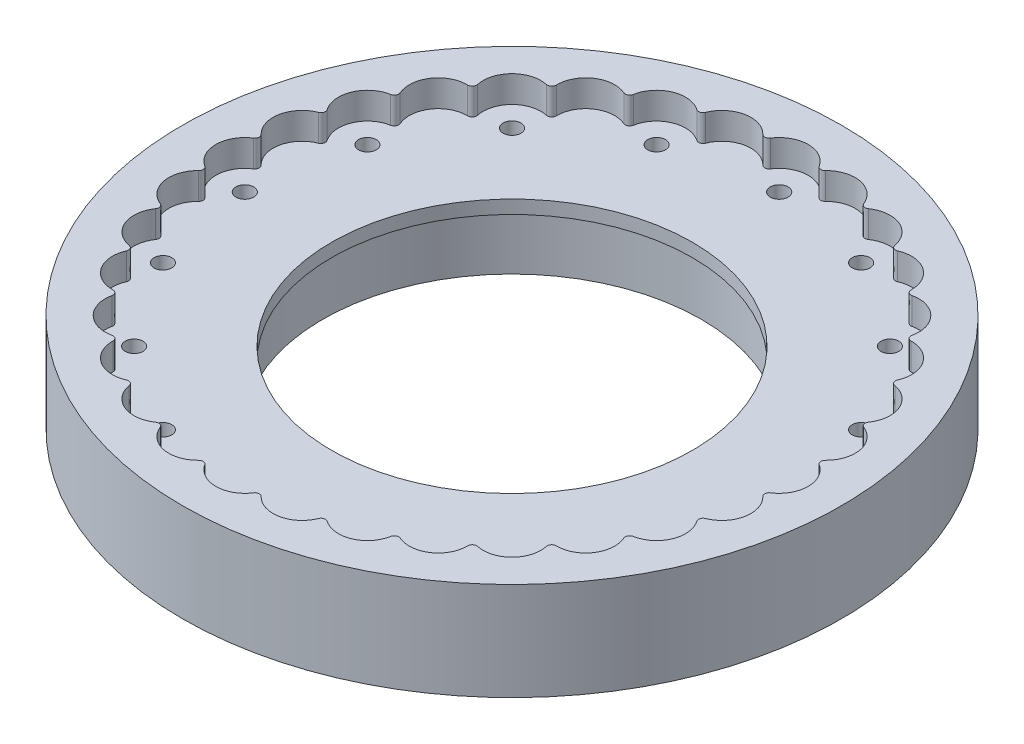
SolidWorks part; units mm, degrees
material "尼龙 101"
ref_plane "前视基准面" through (0, 0, 0) normal (0, 0, 1) x (1, 0, 0)
ref_plane "上视基准面" through (0, 0, 0) normal (0, 1, 0) x (1, 0, 0)
ref_plane "右视基准面" through (0, 0, 0) normal (1, 0, 0) x (0, 0, -1)
sketch "草图1" plane through (0, 0, 0) normal (0, 1, 0) x (1, 0, 0)
  line L0 (-3, 0) -> (-61.8471, 11.7054) construction
  line L1 (-63, 0) -> (-3, 0) construction
  line L2 (-3, 0) -> (-62.7111, 5.881) construction
  line L3 (-61.8471, 11.7054) -> (-80.5752, 15.4307) construction
  line L4 (-63, 0) -> (-84.6703, 0) construction
  arc A23 (51.1029, 1.1255) -> (51, 0) centre (57.2058, 0) ccw construction
  circle A26 centre (-45.4264, 42.4264) radius 6.5 construction
  circle A27 centre (-25.961, 55.4328) radius 6.5 construction
  circle A28 centre (-3, 60) radius 6.5 construction
  circle A29 centre (19.961, 55.4328) radius 6.5 construction
  circle A30 centre (39.4264, 42.4264) radius 6.5 construction
  circle A31 centre (52.4328, 22.961) radius 6.5 construction
  circle A32 centre (57, 0) radius 6.5 construction
  circle A33 centre (52.4328, -22.961) radius 6.5 construction
  circle A34 centre (39.4264, -42.4264) radius 6.5 construction
  circle A35 centre (19.961, -55.4328) radius 6.5 construction
  circle A36 centre (-3, -60) radius 6.5 construction
  circle A37 centre (-25.961, -55.4328) radius 6.5 construction
  circle A38 centre (-45.4264, -42.4264) radius 6.5 construction
  circle A39 centre (-58.4328, -22.961) radius 6.5 construction
  circle A40 centre (-3, 0) radius 74
  circle A42 centre (-3, 0) radius 60 construction
  arc A46 (-68.2222, 12.9735) -> (-65.1785, 6.1241) centre (-61.8471, 11.7054) ccw
  arc A48 (-69.5, 0) -> (-65.1785, 6.1241) centre (-63, 0) cw
  arc A49 (-68.2222, 12.9735) -> (-62.789, 18.1368) centre (-61.8471, 11.7054) cw
  arc A50 (-64.438, 25.4484) -> (-62.789, 18.1368) centre (-58.4328, 22.961) ccw
  arc A51 (-64.438, 25.4484) -> (-58.1019, 29.4526) centre (-58.4328, 22.961) cw
  arc A52 (-58.2927, 36.9454) -> (-58.1019, 29.4526) centre (-52.8882, 33.3342) ccw
  arc A53 (-58.2927, 36.9454) -> (-51.2972, 39.6365) centre (-52.8882, 33.3342) cw
  arc A54 (-50.0226, 47.0226) -> (-51.2972, 39.6365) centre (-45.4264, 42.4264) ccw
  arc A55 (-50.0226, 47.0226) -> (-42.6365, 48.2972) centre (-45.4264, 42.4264) cw
  arc A56 (-39.9454, 55.2927) -> (-42.6365, 48.2972) centre (-36.3342, 49.8882) ccw
  arc A57 (-39.9454, 55.2927) -> (-32.4526, 55.1019) centre (-36.3342, 49.8882) cw
  arc A58 (-28.4484, 61.438) -> (-32.4526, 55.1019) centre (-25.961, 55.4328) ccw
  arc A59 (-28.4484, 61.438) -> (-21.1368, 59.789) centre (-25.961, 55.4328) cw
  arc A60 (-15.9735, 65.2222) -> (-21.1368, 59.789) centre (-14.7054, 58.8471) ccw
  arc A61 (-15.9735, 65.2222) -> (-9.1241, 62.1785) centre (-14.7054, 58.8471) cw
  arc A62 (-3, 66.5) -> (-9.1241, 62.1785) centre (-3, 60) ccw
  arc A63 (-3, 66.5) -> (3.1241, 62.1785) centre (-3, 60) cw
  arc A64 (9.9735, 65.2222) -> (3.1241, 62.1785) centre (8.7054, 58.8471) ccw
  arc A65 (9.9735, 65.2222) -> (15.1368, 59.789) centre (8.7054, 58.8471) cw
  arc A66 (22.4484, 61.438) -> (15.1368, 59.789) centre (19.961, 55.4328) ccw
  arc A67 (22.4484, 61.438) -> (26.4526, 55.1019) centre (19.961, 55.4328) cw
  arc A68 (33.9454, 55.2927) -> (26.4526, 55.1019) centre (30.3342, 49.8882) ccw
  arc A69 (33.9454, 55.2927) -> (36.6365, 48.2972) centre (30.3342, 49.8882) cw
  arc A70 (44.0226, 47.0226) -> (36.6365, 48.2972) centre (39.4264, 42.4264) ccw
  arc A71 (44.0226, 47.0226) -> (45.2972, 39.6365) centre (39.4264, 42.4264) cw
  arc A72 (52.2927, 36.9454) -> (45.2972, 39.6365) centre (46.8882, 33.3342) ccw
  arc A73 (52.2927, 36.9454) -> (52.1019, 29.4526) centre (46.8882, 33.3342) cw
  arc A74 (58.438, 25.4484) -> (52.1019, 29.4526) centre (52.4328, 22.961) ccw
  arc A75 (58.438, 25.4484) -> (56.789, 18.1368) centre (52.4328, 22.961) cw
  arc A76 (62.2222, 12.9735) -> (56.789, 18.1368) centre (55.8471, 11.7054) ccw
  arc A77 (62.2222, 12.9735) -> (59.1785, 6.1241) centre (55.8471, 11.7054) cw
  arc A78 (63.5, 0) -> (59.1785, 6.1241) centre (57, 0) ccw
  arc A79 (63.5, 0) -> (59.1785, -6.1241) centre (57, 0) cw
  arc A80 (62.2222, -12.9735) -> (59.1785, -6.1241) centre (55.8471, -11.7054) ccw
  arc A81 (62.2222, -12.9735) -> (56.789, -18.1368) centre (55.8471, -11.7054) cw
  arc A82 (58.438, -25.4484) -> (56.789, -18.1368) centre (52.4328, -22.961) ccw
  arc A83 (58.438, -25.4484) -> (52.1019, -29.4526) centre (52.4328, -22.961) cw
  arc A84 (52.2927, -36.9454) -> (52.1019, -29.4526) centre (46.8882, -33.3342) ccw
  arc A85 (52.2927, -36.9454) -> (45.2972, -39.6365) centre (46.8882, -33.3342) cw
  arc A86 (44.0226, -47.0226) -> (45.2972, -39.6365) centre (39.4264, -42.4264) ccw
  arc A87 (44.0226, -47.0226) -> (36.6365, -48.2972) centre (39.4264, -42.4264) cw
  arc A88 (33.9454, -55.2927) -> (36.6365, -48.2972) centre (30.3342, -49.8882) ccw
  arc A89 (33.9454, -55.2927) -> (26.4526, -55.1019) centre (30.3342, -49.8882) cw
  arc A90 (22.4484, -61.438) -> (26.4526, -55.1019) centre (19.961, -55.4328) ccw
  arc A91 (22.4484, -61.438) -> (15.1368, -59.789) centre (19.961, -55.4328) cw
  arc A92 (9.9735, -65.2222) -> (15.1368, -59.789) centre (8.7054, -58.8471) ccw
  arc A93 (9.9735, -65.2222) -> (3.1241, -62.1785) centre (8.7054, -58.8471) cw
  arc A94 (-3, -66.5) -> (3.1241, -62.1785) centre (-3, -60) ccw
  arc A95 (-3, -66.5) -> (-9.1241, -62.1785) centre (-3, -60) cw
  arc A96 (-15.9735, -65.2222) -> (-9.1241, -62.1785) centre (-14.7054, -58.8471) ccw
  arc A97 (-15.9735, -65.2222) -> (-21.1368, -59.789) centre (-14.7054, -58.8471) cw
  arc A98 (-28.4484, -61.438) -> (-21.1368, -59.789) centre (-25.961, -55.4328) ccw
  arc A99 (-28.4484, -61.438) -> (-32.4526, -55.1019) centre (-25.961, -55.4328) cw
  arc A100 (-39.9454, -55.2927) -> (-32.4526, -55.1019) centre (-36.3342, -49.8882) ccw
  arc A101 (-39.9454, -55.2927) -> (-42.6365, -48.2972) centre (-36.3342, -49.8882) cw
  arc A102 (-50.0226, -47.0226) -> (-42.6365, -48.2972) centre (-45.4264, -42.4264) ccw
  arc A103 (-50.0226, -47.0226) -> (-51.2972, -39.6365) centre (-45.4264, -42.4264) cw
  arc A104 (-58.2927, -36.9454) -> (-51.2972, -39.6365) centre (-52.8882, -33.3342) ccw
  arc A105 (-58.2927, -36.9454) -> (-58.1019, -29.4526) centre (-52.8882, -33.3342) cw
  arc A106 (-64.438, -25.4484) -> (-58.1019, -29.4526) centre (-58.4328, -22.961) ccw
  arc A107 (-64.438, -25.4484) -> (-62.789, -18.1368) centre (-58.4328, -22.961) cw
  arc A108 (-68.2222, -12.9735) -> (-62.789, -18.1368) centre (-61.8471, -11.7054) ccw
  arc A109 (-68.2222, -12.9735) -> (-65.1785, -6.1241) centre (-61.8471, -11.7054) cw
  arc A110 (-69.5, 0) -> (-65.1785, -6.1241) centre (-63, 0) ccw
  spline S0 degree 4 poles (46.5379, 25.7372) (46.4141, 25.4265) (46.2214, 24.8455) (46.0453, 23.97) (46.0305, 22.7997) (46.2124, 21.7023) (46.5944, 20.6304) (47.1781, 19.6256) (47.8576, 18.8426) (48.5552, 18.26) (49.1821, 17.8581) (49.7006, 17.5881) (50.2292, 17.3676) (50.7615, 17.19) (51.2467, 17.0604) (51.6756, 16.9442) (52.1157, 16.7843) (52.5471, 16.5748) (53.011, 16.2813) (53.5578, 15.8417) (54.0998, 15.2905) (54.8463, 14.3188) (55.4686, 13.069) (55.8643, 11.6469) (55.963, 10.2274) (55.8937, 9.2229) (55.7314, 8.3871) (55.5299, 7.7199) (55.2718, 7.103) (54.9628, 6.5421) (54.6, 6.0376) (54.1839, 5.6019) (53.729, 5.2398) (53.2959, 4.8829) (52.8541, 4.4702) (52.42, 3.9903) (52.024, 3.4526) (51.6787, 2.8581) (51.4223, 2.2845) (51.2601, 1.8044) (51.1585, 1.4093) (51.0974, 1.1068) (51.0631, 0.8925) (51.0397, 0.7088) (51.0244, 0.5571) (51.0146, 0.4347) (51.0053, 0.2754) (51, 0.0893) (50.9991, -0.0325) (51.0033, -0.2118) (51.0104, -0.3723) (51.0237, -0.5582) (51.0467, -0.7767) (51.0935, -1.1015) (51.1814, -1.5223) (51.3208, -2.0042) (51.5289, -2.5363) (51.7967, -3.0719) (52.1288, -3.6024) (52.5013, -4.0845) (52.9041, -4.5182) (53.3092, -4.8924) (53.702, -5.2183) (54.1137, -5.5446) (54.4991, -5.9242) (54.8403, -6.3624) (55.1378, -6.8475) (55.4263, -7.4461) (55.6786, -8.1632) (55.8744, -9.0445) (55.9607, -10.0854) (55.902, -11.1727) (55.6837, -12.2843) (55.3275, -13.3134) (54.856, -14.2458) (54.3439, -14.9904) (53.8416, -15.5634) (53.3534, -16.0123) (52.9029, -16.3539) (52.4611, -16.6202) (52.0385, -16.8165) (51.6463, -16.9514) (51.2956, -17.047) (50.9168, -17.149) (50.5132, -17.271) (50.0892, -17.4238) (49.6494, -17.6158) (49.0833, -17.9121) (48.4035, -18.3646) (47.6718, -19.0234) (46.9704, -19.9376) (46.436, -20.9941) (46.1117, -22.1269) (46.0124, -23.2422) (46.1036, -24.2957) (46.3078, -25.1327) (46.5435, -25.7773) (46.7581, -26.2481) (46.914, -26.5603) (47.0718, -26.8714) (47.2362, -27.2113) (47.3981, -27.6474) (47.5243, -28.1866) (47.5924, -28.7663) (47.6026, -29.4384) (47.5301, -30.1963) (47.3381, -31.083) (46.9787, -32.0726) (46.3109, -33.3348) (45.4042, -34.4509) (44.347, -35.3429) (43.2664, -35.9432) (42.5437, -36.236) (41.8612, -36.4237) (41.3142, -36.5096) (40.8308, -36.531) (40.3614, -36.5031) (39.9223, -36.4373) (39.429, -36.3568) (38.8747, -36.2998) (38.3065, -36.2819) (37.7271, -36.3124) (36.99, -36.4173) (36.0942, -36.6625) (35.1251, -37.109) (34.1566, -37.8104) (33.3468, -38.6733) (32.7332, -39.6305) (32.365, -40.5265) (32.1683, -41.3066) (32.0778, -41.929) (32.0418, -42.3994) (32.0358, -42.8432) (32.0497, -43.2589) (32.0714, -43.6463) (32.0826, -44.0066) (32.0632, -44.417) (31.9953, -44.8732) (31.8342, -45.5014) (31.5334, -46.239) (31.0863, -47.0125) (30.2784, -48.0426) (29.2767, -48.9308) (28.0765, -49.659) (26.7888, -50.1357) (25.7857, -50.3555) (24.9142, -50.4297) (24.1917, -50.4106) (23.5355, -50.3216) (22.9511, -50.1778) (22.4651, -49.9941) (22.0782, -49.7927) (21.7795, -49.6071) (21.5546, -49.4615) (21.2725, -49.2809) (20.928, -49.0738) (20.5013, -48.8474) (19.9846, -48.6223) (19.434, -48.4365) (18.8519, -48.2978) (18.1069, -48.1932) (17.1874, -48.1824) (16.1397, -48.343) (15.0305, -48.7429) (14.036, -49.3297) (13.2407, -50.0153) (12.6167, -50.7563) (12.1857, -51.4457) (11.8991, -52.0281) (11.6878, -52.5417) (11.526, -52.9744) (11.3359, -53.4202) (11.0812, -53.8588) (10.7673, -54.2823) (10.3968, -54.6857) (9.919, -55.118) (9.3192, -55.5548) (8.5533, -55.9873) (7.6098, -56.3665) (6.5728, -56.6314) (5.4562, -56.7578) (4.3706, -56.7287) (3.3372, -56.5582) (2.4735, -56.2932) (1.7785, -55.9874) (1.2003, -55.6539) (0.7315, -55.3183) (0.3297, -54.9579) (-0.0031, -54.5808) (-0.2691, -54.1986) (-0.4996, -53.8375) (-0.799, -53.3974) (-1.189, -52.8945) (-1.7518, -52.3018) (-2.5487, -51.6731) (-3.5127, -51.1471) (-4.6341, -50.7864) (-5.8197, -50.642) (-6.9885, -50.7226) (-8.0385, -50.9971) (-8.9494, -51.4066) (-9.6407, -51.8441) (-10.1588, -52.2535) (-10.5841, -52.6447) (-10.8891, -52.9527) (-11.1549, -53.2129) (-11.4512, -53.4676) (-11.7835, -53.7079) (-12.2085, -53.9529) (-12.7305, -54.1823) (-13.3637, -54.3899) (-14.1104, -54.5474) (-15.0125, -54.6285) (-16.0592, -54.5811) (-17.1309, -54.3847) (-18.204, -54.0281) (-19.1516, -53.5586) (-19.9687, -53.0108) (-20.7121, -52.3651) (-21.2707, -51.7315) (-21.7011, -51.088) (-21.9912, -50.4891) (-22.155, -50.0306) (-22.2585, -49.5926) (-22.3227, -49.1847) (-22.3899, -48.7713) (-22.4739, -48.3546) (-22.6085, -47.8313) (-22.8424, -47.1546) (-23.2318, -46.3575) (-23.8544, -45.4791) (-24.6871, -44.6677) (-25.6692, -44.0188) (-26.6389, -43.6178) (-27.5154, -43.4106) (-28.2524, -43.3323) (-28.8472, -43.3254) (-29.4322, -43.3725) (-30.003, -43.4693) (-30.5614, -43.6126) (-31.0373, -43.7728) (-31.4387, -43.9271) (-31.8427, -44.0792) (-32.2579, -44.2061) (-32.7611, -44.2963) (-33.347, -44.3297) (-34.0225, -44.2957) (-34.7782, -44.1696) (-35.6535, -43.9116) (-36.6179, -43.4757) (-37.7704, -42.7458) (-38.7933, -41.7926) (-39.611, -40.6949) (-40.1395, -39.6116) (-40.3976, -38.8546) (-40.5426, -38.2008) (-40.6112, -37.6643) (-40.6244, -37.1634) (-40.5888, -36.7038) (-40.513, -36.2896) (-40.4169, -35.9209) (-40.2866, -35.4356) (-40.1742, -34.9317) (-40.0977, -34.4072) (-40.055, -33.7098) (-40.0823, -32.9434) (-40.242, -32.0266) (-40.6161, -30.9905) (-41.1976, -29.9862) (-41.9718, -29.089) (-42.813, -28.4312) (-43.6374, -27.9836) (-44.3396, -27.7115) (-44.9036, -27.5499) (-45.4676, -27.4392) (-46.0267, -27.3726) (-46.531, -27.3441) (-46.9786, -27.3217) (-47.4491, -27.2608) (-47.924, -27.1472) (-48.4491, -26.9557) (-49.0877, -26.6351) (-49.7446, -26.2008) (-50.6925, -25.3887) (-51.5674, -24.2757) (-52.2468, -22.9494) (-52.6787, -21.3876) (-52.7938, -20.2381) (-52.7415, -19.2513) (-52.5869, -18.4477) (-52.4194, -17.8829) (-52.2031, -17.3696) (-51.9445, -16.9122) (-51.6489, -16.5156) (-51.3534, -16.1582) (-51.0001, -15.7004) (-50.6155, -15.1236) (-50.215, -14.3486) (-49.8747, -13.3327) (-49.7104, -12.2175) (-49.7626, -11.0381) (-50.0365, -9.8863) (-50.5035, -8.838) (-51.1016, -7.968) (-51.767, -7.2731) (-52.3746, -6.7892) (-52.8873, -6.4554) (-53.352, -6.1961) (-53.7558, -5.9914) (-54.1811, -5.7701) (-54.6019, -5.4873) (-55.0061, -5.1386) (-55.388, -4.7281) (-55.8029, -4.184) (-56.2163, -3.4883) (-56.5934, -2.616) (-56.8794, -1.5636) (-57.0192, -0.4644) (-57.0056, 0.6609) (-56.8431, 1.7289) (-56.5512, 2.7215) (-56.1864, 3.5378) (-55.8005, 4.1844) (-55.4038, 4.7095) (-55.0213, 5.1241) (-54.6067, 5.4849) (-54.1623, 5.7832) (-53.6999, 6.019) (-53.2522, 6.2482) (-52.7801, 6.5213) (-52.2943, 6.8511) (-51.7159, 7.3247) (-51.0958, 7.9792) (-50.5093, 8.8286) (-50.0309, 9.8972) (-49.7598, 11.0441) (-49.7119, 12.2402) (-49.8762, 13.3181) (-50.1782, 14.2422) (-50.5297, 14.9617) (-50.8583, 15.4946) (-51.1503, 15.8971) (-51.3791, 16.1864) (-51.6107, 16.4733) (-51.8529, 16.7821) (-52.1097, 17.1857) (-52.3487, 17.6957) (-52.5356, 18.2511) (-52.6793, 18.8847) (-52.763, 19.5933) (-52.7701, 20.454) (-52.6495, 21.4551) (-52.3771, 22.4981) (-51.9324, 23.5552) (-51.3729, 24.4924) (-50.7281, 25.3031) (-49.9819, 26.0211) (-49.2536, 26.5457) (-48.5459, 26.9194) (-47.9336, 27.1417) (-47.4843, 27.2532) (-47.0763, 27.3113) (-46.7156, 27.3356) (-46.3267, 27.3549) (-45.9101, 27.3865) (-45.4675, 27.4417) (-45.0015, 27.5305) (-44.3901, 27.6912) (-43.6335, 27.9763) (-42.7808, 28.447) (-41.8967, 29.1702) (-41.1366, 30.0712) (-40.5592, 31.0993) (-40.2209, 32.1183) (-40.0728, 33.0677) (-40.0563, 33.8576) (-40.1067, 34.4963) (-40.2075, 35.0962) (-40.3418, 35.6563) (-40.4802, 36.1417) (-40.5678, 36.5674) (-40.6138, 37.0012) (-40.6228, 37.442) (-40.5823, 37.957) (-40.4594, 38.6248) (-40.2357, 39.3609) (-39.8665, 40.1996) (-39.3093, 41.105) (-38.5945, 41.9688) (-37.7193, 42.7584) (-36.7891, 43.3798) (-35.8364, 43.84) (-34.9691, 44.1216) (-34.2184, 44.27) (-33.545, 44.3264) (-32.9584, 44.3148) (-32.4068, 44.2406) (-31.8988, 44.1039) (-31.436, 43.9247) (-30.9987, 43.7594) (-30.449, 43.5789) (-29.7785, 43.4164) (-28.9191, 43.3079) (-27.8569, 43.3383) (-26.757, 43.5667) (-25.6692, 44.0207) (-24.684, 44.6726) (-23.8603, 45.4711) (-23.2924, 46.269) (-22.9216, 46.9921) (-22.6921, 47.5848) (-22.5511, 48.0407) (-22.4467, 48.4768) (-22.3698, 48.8893) (-22.3091, 49.2753) (-22.2491, 49.6326) (-22.1523, 50.0344) (-21.9978, 50.4724) (-21.7764, 50.9361) (-21.482, 51.4161) (-21.0854, 51.9441) (-20.5679, 52.4988) (-19.8818, 53.0808) (-19.0059, 53.6423) (-18.0145, 54.1038) (-16.9178, 54.4377) (-15.8549, 54.6016) (-14.8516, 54.6199) (-13.9999, 54.5266) (-13.3064, 54.3732) (-12.6928, 54.1684) (-12.1604, 53.929) (-11.6778, 53.643) (-11.3015, 53.3503) (-11.0187, 53.0802) (-10.7585, 52.8208) (-10.4964, 52.563) (-10.1304, 52.2302) (-9.6404, 51.8467) (-8.9692, 51.4191) (-8.0913, 51.0165) (-7.0449, 50.7309) (-5.8547, 50.64) (-4.6842, 50.7757) (-3.5637, 51.1281) (-2.6486, 51.6152) (-1.9245, 52.1589) (-1.3864, 52.6821) (-1.0025, 53.1293) (-0.6771, 53.5709) (-0.3982, 53.9941) (-0.1162, 54.4338) (0.2241, 54.8506) (0.6253, 55.2305) (1.0772, 55.5722) (1.6416, 55.9168) (2.3267, 56.2378) (3.1797, 56.5198) (4.2016, 56.7104) (5.2866, 56.7631) (6.4144, 56.66) (7.4766, 56.4105) (8.4562, 56.0346) (9.2521, 55.5984) (9.8752, 55.154) (10.3724, 54.7109) (10.7582, 54.2944) (11.0488, 53.9039) (11.2569, 53.556) (11.4258, 53.2121) (11.5625, 52.8773) (11.7103, 52.4828) (11.9209, 51.9813) (12.1928, 51.4389) (12.5985, 50.7878) (13.1988, 50.0572) (13.9876, 49.3606) (14.9807, 48.7666) (16.0976, 48.3562) (17.2682, 48.1654) (18.3284, 48.1967) (19.244, 48.3746) (19.9605, 48.6113) (20.5094, 48.8503) (21.0146, 49.1208) (21.4217, 49.3736) (21.7644, 49.5994) (22.061, 49.7799) (22.3115, 49.9131) (22.6419, 50.061) (23.0591, 50.2055) (23.561, 50.3258) (24.2389, 50.4157) (25.0178, 50.4296) (25.9392, 50.3338) (26.9809, 50.0765) (28.32, 49.538) (29.5308, 48.7459) (30.5312, 47.7796) (31.2405, 46.7598) (31.6056, 46.0664) (31.8606, 45.4025) (31.9997, 44.8638) (32.0673, 44.3826) (32.0836, 43.9106) (32.0614, 43.4651) (32.0348, 42.9634) (32.0393, 42.4031) (32.0856, 41.8333) (32.182, 41.2578) (32.3713, 40.5332) (32.7195, 39.6672) (33.2739, 38.7585) (34.0745, 37.8856) (35.0067, 37.1899) (35.9971, 36.6968) (36.8947, 36.432) (37.6572, 36.3175) (38.3592, 36.2814) (38.8924, 36.299) (39.4083, 36.3557) (39.9069, 36.4338) (40.2839, 36.4925) (40.7045, 36.5289) (41.1671, 36.5204) (41.6662, 36.4586) (42.1957, 36.337) (42.8347, 36.1271) (43.5651, 35.7931) (44.3633, 35.2983) (45.188, 34.6103) (46.1279, 33.5815) (46.8494, 32.4192) (47.337, 31.1804) (47.5589, 30.0001) (47.6088, 29.2392) (47.5762, 28.5668) (47.4863, 27.9897) (47.349, 27.4996) (47.1843, 27.0997) (46.9931, 26.7142) (46.7974, 26.333) (46.5867, 25.8792) (46.3831, 25.3424) (46.2237, 24.7888) (46.1116, 24.2161) (46.0512, 23.6278) (46.0449, 22.8915) (46.1493, 22.0014) (46.4363, 20.9879) (46.9745, 19.9251) (47.7041, 18.9865) (48.4998, 18.2848) (49.285, 17.7868) (49.9686, 17.4674) (50.5132, 17.2692) (51.0085, 17.1221) (51.4478, 17.0085) (51.912, 16.8692) (52.3842, 16.6623) (52.8554, 16.3864) (53.3182, 16.0422) (53.7955, 15.609) (54.2709, 15.0778) (54.7703, 14.3808) (55.2461, 13.4987) (55.6279, 12.4872) (55.8786, 11.3552) (55.9619, 10.2497) (55.8955, 9.1942) (55.7154, 8.2993) (55.4758, 7.57) (55.1961, 6.9567) (54.9032, 6.4546) (54.5797, 6.0202) (54.2341, 5.6566) (53.8813, 5.3592) (53.5523, 5.0956) (53.2287, 4.8192) (52.9161, 4.5249) (52.5434, 4.1311) (52.1808, 3.6766) (51.8445, 3.1605) (51.579, 2.6398) (51.4091, 2.232) (51.2991, 1.9115) (51.2333, 1.6918) (51.1844, 1.5058) (51.1465, 1.3427) (51.1136, 1.185) (51.0924, 1.0702) (51.0671, 0.9132) (51.0452, 0.7545) (51.0245, 0.5678) (51.0076, 0.3469) (50.9975, 0.0834) (51.0008, -0.2155) (51.0227, -0.5894) (51.078, -1.035) (51.1839, -1.5486) (51.4036, -2.2603) (51.7236, -2.9659) (52.1483, -3.6478) (52.6384, -4.2427) (53.0557, -4.6645) (53.4116, -4.9778) (53.6865, -5.203) (53.9622, -5.4272) (54.1981, -5.6295) (54.4282, -5.8597) (54.6955, -6.1751) (54.9531, -6.5374) (55.213, -6.9884) (55.4926, -7.613) (55.7287, -8.3512) (55.9038, -9.2579) (55.962, -10.3279) (55.8389, -11.7595) (55.3724, -13.3703) (54.624, -14.7129) (53.6976, -15.737) (52.9621, -16.3159) (52.4954, -16.6036) (52.0618, -16.8071) (51.6202, -16.9607) (51.191, -17.0744) (50.7066, -17.2066) (50.1754, -17.3878) (49.6487, -17.6127) (49.1328, -17.887) (48.5098, -18.2942) (47.8181, -18.8824) (47.1451, -19.672) (46.5697, -20.6837) (46.1967, -21.7626) (46.0167, -22.923) (46.0486, -23.8183) (46.1486, -24.4241) (46.2252, -24.7497) knots 0 0 0 0 0 0.002873 0.005251 0.007629 0.010007 0.012383 0.014979 0.017557 0.018862 0.020166 0.02137 0.022574 0.023779 0.024983 0.025687 0.026391 0.027799 0.029095 0.030392 0.032409 0.034427 0.039593 0.04229 0.044987 0.046603 0.04822 0.049593 0.050967 0.05234 0.053712 0.054918 0.056125 0.057331 0.058537 0.060108 0.061678 0.063057 0.064435 0.065497 0.066028 0.066559 0.06709 0.067355 0.067621 0.067886 0.068152 0.068683 0.069002 0.069321 0.06964 0.069959 0.070597 0.071235 0.072446 0.073657 0.074899 0.076141 0.077584 0.079028 0.080125 0.081222 0.082319 0.083415 0.084637 0.085858 0.087078 0.088298 0.090338 0.092377 0.094812 0.097246 0.099663 0.10208 0.104139 0.106198 0.107406 0.108614 0.109832 0.111049 0.11183 0.112611 0.113392 0.114172 0.115202 0.116232 0.117262 0.118292 0.120689 0.123232 0.125678 0.128137 0.130806 0.133296 0.135241 0.137186 0.138186 0.139185 0.139685 0.140185 0.141184 0.142428 0.143672 0.144932 0.146191 0.148196 0.150201 0.152706 0.155211 0.160423 0.162457 0.164492 0.1658 0.167108 0.168529 0.169239 0.169949 0.171145 0.172341 0.173537 0.174732 0.176026 0.17732 0.179927 0.182686 0.185136 0.187531 0.190041 0.192403 0.193415 0.194428 0.195441 0.196454 0.197228 0.198002 0.198776 0.19955 0.200754 0.201958 0.204338 0.206371 0.208404 0.213175 0.21576 0.218345 0.220159 0.221973 0.223259 0.224544 0.225839 0.227134 0.22771 0.228286 0.228861 0.229437 0.230589 0.23174 0.233008 0.234276 0.235576 0.236876 0.239463 0.24215 0.244626 0.246945 0.249334 0.251127 0.25292 0.253913 0.254906 0.255899 0.256891 0.258072 0.259252 0.260421 0.26159 0.263602 0.265615 0.267959 0.270303 0.272772 0.275241 0.277259 0.279276 0.280514 0.281752 0.282987 0.284221 0.285142 0.286063 0.286984 0.287905 0.289715 0.291526 0.293988 0.296594 0.299097 0.301588 0.304193 0.306602 0.30837 0.310139 0.311204 0.312269 0.313333 0.313866 0.314398 0.315625 0.316852 0.318071 0.31929 0.321343 0.323396 0.325831 0.328267 0.330675 0.333082 0.33489 0.336697 0.339117 0.340317 0.341518 0.342405 0.343292 0.344179 0.345066 0.346004 0.346943 0.34882 0.351209 0.353598 0.356148 0.358755 0.361262 0.362562 0.363862 0.365114 0.366367 0.367599 0.368831 0.370063 0.370679 0.371295 0.372541 0.373788 0.375058 0.376329 0.378343 0.380357 0.382876 0.385394 0.390023 0.392288 0.394554 0.395716 0.396878 0.398037 0.399195 0.400014 0.400832 0.40165 0.402469 0.404333 0.405265 0.406198 0.408469 0.410909 0.413223 0.415614 0.418392 0.421029 0.422338 0.423647 0.424855 0.426064 0.427272 0.428481 0.429197 0.429913 0.431345 0.432667 0.433988 0.436042 0.438096 0.443359 0.446048 0.448738 0.451962 0.453234 0.454505 0.45576 0.457015 0.458011 0.459008 0.460004 0.461001 0.462979 0.464957 0.467475 0.470169 0.472606 0.475041 0.477593 0.479975 0.481628 0.48328 0.484253 0.485226 0.486199 0.487172 0.488371 0.489571 0.490776 0.491982 0.494244 0.496506 0.498914 0.501323 0.503735 0.506146 0.508167 0.510188 0.511396 0.512603 0.513815 0.515027 0.516108 0.517189 0.51827 0.519352 0.520791 0.52223 0.524684 0.527074 0.529614 0.532236 0.534748 0.537299 0.538929 0.540559 0.541615 0.542671 0.5432 0.543728 0.544784 0.546042 0.547299 0.548555 0.549811 0.551616 0.55342 0.555935 0.55845 0.560847 0.563243 0.565285 0.567326 0.569719 0.570928 0.572137 0.572913 0.573689 0.574466 0.575242 0.57626 0.577279 0.578297 0.579315 0.581688 0.58421 0.586622 0.589075 0.591763 0.59428 0.595792 0.597303 0.59854 0.599777 0.601014 0.602251 0.602878 0.603505 0.604759 0.606034 0.607308 0.609332 0.611355 0.613885 0.616415 0.618932 0.62145 0.623464 0.625478 0.626745 0.628012 0.629262 0.630511 0.631516 0.63252 0.633525 0.634529 0.636485 0.63844 0.640943 0.643622 0.646079 0.648508 0.65104 0.653425 0.654449 0.655473 0.656498 0.657522 0.6583 0.659078 0.659856 0.660634 0.661848 0.663061 0.664263 0.665465 0.667516 0.669566 0.671973 0.674379 0.676883 0.679386 0.681182 0.682977 0.684228 0.685479 0.686732 0.687985 0.689038 0.689564 0.690091 0.691143 0.692196 0.693813 0.69543 0.697969 0.700465 0.703081 0.705626 0.708032 0.710501 0.711942 0.713382 0.714471 0.715561 0.71665 0.71774 0.718956 0.720172 0.721386 0.7226 0.72463 0.72666 0.729084 0.731507 0.733934 0.736361 0.738429 0.740496 0.74171 0.742923 0.744145 0.745367 0.745884 0.746401 0.747436 0.748471 0.749506 0.751074 0.752643 0.755051 0.757604 0.760067 0.76253 0.765219 0.767733 0.769126 0.770518 0.771694 0.77287 0.774046 0.774634 0.775222 0.775853 0.776483 0.777743 0.779011 0.780279 0.78235 0.784422 0.786946 0.789471 0.794708 0.796752 0.798796 0.800112 0.801427 0.802853 0.803566 0.804278 0.805481 0.806683 0.807885 0.809088 0.810389 0.811691 0.814312 0.817081 0.819476 0.821805 0.824257 0.826538 0.827478 0.828417 0.830295 0.831114 0.831934 0.832754 0.833574 0.834738 0.835902 0.837068 0.838235 0.840511 0.842786 0.845111 0.847435 0.852449 0.854454 0.85646 0.857724 0.858988 0.860229 0.86147 0.862084 0.862698 0.863926 0.865154 0.866381 0.867626 0.868871 0.870163 0.871456 0.873945 0.876546 0.879162 0.881628 0.884101 0.885613 0.887126 0.888101 0.889076 0.890051 0.891027 0.89226 0.893494 0.894734 0.895974 0.897792 0.899609 0.902086 0.904563 0.90705 0.909538 0.91158 0.913622 0.914871 0.916121 0.917365 0.918608 0.919515 0.920421 0.921327 0.922233 0.92317 0.924108 0.925983 0.92722 0.928456 0.92912 0.929784 0.930116 0.930449 0.930781 0.931113 0.931435 0.931756 0.932078 0.9324 0.933043 0.933686 0.934329 0.934972 0.936259 0.937543 0.938828 0.941365 0.942893 0.944422 0.94544 0.946458 0.946967 0.947476 0.948494 0.949127 0.94976 0.951026 0.952309 0.953592 0.955632 0.957672 0.960221 0.962771 0.967934 0.971965 0.973261 0.974557 0.975962 0.976665 0.977367 0.978572 0.979776 0.980981 0.982185 0.983488 0.984791 0.987368 0.989961 0.992349 0.994736 0.997126 1 1 1 1 1 construction
  spline S1 degree 4 poles (51, 0) (51, -0.032) (51.0006, -0.0965) (51.0033, -0.2118) (51.0104, -0.3723) (51.0237, -0.5582) (51.0467, -0.7767) (51.0935, -1.1015) (51.1814, -1.5223) (51.3208, -2.0042) (51.5289, -2.5363) (51.7967, -3.0719) (52.1288, -3.6024) (52.5013, -4.0845) (52.9041, -4.5182) (53.3092, -4.8924) (53.702, -5.2183) (54.1137, -5.5446) (54.4991, -5.9242) (54.8403, -6.3624) (55.1378, -6.8475) (55.4263, -7.4461) (55.6786, -8.1632) (55.8744, -9.0445) (55.9607, -10.0854) (55.902, -11.1727) (55.6837, -12.2843) (55.3275, -13.3134) (54.856, -14.2458) (54.3439, -14.9904) (53.8416, -15.5634) (53.3534, -16.0123) (52.9029, -16.3539) (52.4611, -16.6202) (52.0385, -16.8165) (51.6463, -16.9514) (51.2956, -17.047) (50.9168, -17.149) (50.5132, -17.271) (50.0892, -17.4238) (49.6494, -17.6158) (49.0833, -17.9121) (48.4035, -18.3646) (47.6718, -19.0234) (46.9704, -19.9376) (46.436, -20.9941) (46.1117, -22.1269) (46.0124, -23.2422) (46.1036, -24.2957) (46.3078, -25.1327) (46.5435, -25.7773) (46.7581, -26.2481) (46.914, -26.5603) (47.0718, -26.8714) (47.2362, -27.2113) (47.3981, -27.6474) (47.5243, -28.1866) (47.5924, -28.7663) (47.6026, -29.4384) (47.5301, -30.1963) (47.3381, -31.083) (46.9787, -32.0726) (46.3109, -33.3348) (45.4042, -34.4509) (44.347, -35.3429) (43.2664, -35.9432) (42.5437, -36.236) (41.8612, -36.4237) (41.3142, -36.5096) (40.8308, -36.531) (40.3614, -36.5031) (39.9223, -36.4373) (39.429, -36.3568) (38.8747, -36.2998) (38.3065, -36.2819) (37.7271, -36.3124) (36.99, -36.4173) (36.0942, -36.6625) (35.1251, -37.109) (34.1566, -37.8104) (33.3468, -38.6733) (32.7332, -39.6305) (32.365, -40.5265) (32.1683, -41.3066) (32.0778, -41.929) (32.0418, -42.3994) (32.0358, -42.8432) (32.0497, -43.2589) (32.0714, -43.6463) (32.0826, -44.0066) (32.0632, -44.417) (31.9953, -44.8732) (31.8342, -45.5014) (31.5334, -46.239) (31.0863, -47.0125) (30.2784, -48.0426) (29.2767, -48.9308) (28.0765, -49.659) (26.7888, -50.1357) (25.7857, -50.3555) (24.9142, -50.4297) (24.1917, -50.4106) (23.5355, -50.3216) (22.9511, -50.1778) (22.4651, -49.9941) (22.0782, -49.7927) (21.7795, -49.6071) (21.5546, -49.4615) (21.2725, -49.2809) (20.928, -49.0738) (20.5013, -48.8474) (19.9846, -48.6223) (19.434, -48.4365) (18.8519, -48.2978) (18.1069, -48.1932) (17.1874, -48.1824) (16.1397, -48.343) (15.0305, -48.7429) (14.036, -49.3297) (13.2407, -50.0153) (12.6167, -50.7563) (12.1857, -51.4457) (11.8991, -52.0281) (11.6878, -52.5417) (11.526, -52.9744) (11.3359, -53.4202) (11.0812, -53.8588) (10.7673, -54.2823) (10.3968, -54.6857) (9.919, -55.118) (9.3192, -55.5548) (8.5533, -55.9873) (7.6098, -56.3665) (6.5728, -56.6314) (5.4562, -56.7578) (4.3706, -56.7287) (3.3372, -56.5582) (2.4735, -56.2932) (1.7785, -55.9874) (1.2003, -55.6539) (0.7315, -55.3183) (0.3297, -54.9579) (-0.0031, -54.5808) (-0.2691, -54.1986) (-0.4996, -53.8375) (-0.799, -53.3974) (-1.189, -52.8945) (-1.7518, -52.3018) (-2.5487, -51.6731) (-3.5127, -51.1471) (-4.6341, -50.7864) (-5.8197, -50.642) (-6.9885, -50.7226) (-8.0385, -50.9971) (-8.9494, -51.4066) (-9.6407, -51.8441) (-10.1588, -52.2535) (-10.5841, -52.6447) (-10.8891, -52.9527) (-11.1549, -53.2129) (-11.4512, -53.4676) (-11.7835, -53.7079) (-12.2085, -53.9529) (-12.7305, -54.1823) (-13.3637, -54.3899) (-14.1104, -54.5474) (-15.0125, -54.6285) (-16.0592, -54.5811) (-17.1309, -54.3847) (-18.204, -54.0281) (-19.1516, -53.5586) (-19.9687, -53.0108) (-20.7121, -52.3651) (-21.2707, -51.7315) (-21.7011, -51.088) (-21.9912, -50.4891) (-22.155, -50.0306) (-22.2585, -49.5926) (-22.3227, -49.1847) (-22.3899, -48.7713) (-22.4739, -48.3546) (-22.6085, -47.8313) (-22.8424, -47.1546) (-23.2318, -46.3575) (-23.8544, -45.4791) (-24.6871, -44.6677) (-25.6692, -44.0188) (-26.6389, -43.6178) (-27.5154, -43.4106) (-28.2524, -43.3323) (-28.8472, -43.3254) (-29.4322, -43.3725) (-30.003, -43.4693) (-30.5614, -43.6126) (-31.0373, -43.7728) (-31.4387, -43.9271) (-31.8427, -44.0792) (-32.2579, -44.2061) (-32.7611, -44.2963) (-33.347, -44.3297) (-34.0225, -44.2957) (-34.7782, -44.1696) (-35.6535, -43.9116) (-36.6179, -43.4757) (-37.7704, -42.7458) (-38.7933, -41.7926) (-39.611, -40.6949) (-40.1395, -39.6116) (-40.3976, -38.8546) (-40.5426, -38.2008) (-40.6112, -37.6643) (-40.6244, -37.1634) (-40.5888, -36.7038) (-40.513, -36.2896) (-40.4169, -35.9209) (-40.2866, -35.4356) (-40.1742, -34.9317) (-40.0977, -34.4072) (-40.055, -33.7098) (-40.0823, -32.9434) (-40.242, -32.0266) (-40.6161, -30.9905) (-41.1976, -29.9862) (-41.9718, -29.089) (-42.813, -28.4312) (-43.6374, -27.9836) (-44.3396, -27.7115) (-44.9036, -27.5499) (-45.4676, -27.4392) (-46.0267, -27.3726) (-46.531, -27.3441) (-46.9786, -27.3217) (-47.4491, -27.2608) (-47.924, -27.1472) (-48.4491, -26.9557) (-49.0877, -26.6351) (-49.7446, -26.2008) (-50.6925, -25.3887) (-51.5674, -24.2757) (-52.2468, -22.9494) (-52.6787, -21.3876) (-52.7938, -20.2381) (-52.7415, -19.2513) (-52.5869, -18.4477) (-52.4194, -17.8829) (-52.2031, -17.3696) (-51.9445, -16.9122) (-51.6489, -16.5156) (-51.3534, -16.1582) (-51.0001, -15.7004) (-50.6155, -15.1236) (-50.215, -14.3486) (-49.8747, -13.3327) (-49.7104, -12.2175) (-49.7626, -11.0381) (-50.0365, -9.8863) (-50.5035, -8.838) (-51.1016, -7.968) (-51.767, -7.2731) (-52.3746, -6.7892) (-52.8873, -6.4554) (-53.352, -6.1961) (-53.7558, -5.9914) (-54.1811, -5.7701) (-54.6019, -5.4873) (-55.0061, -5.1386) (-55.388, -4.7281) (-55.8029, -4.184) (-56.2163, -3.4883) (-56.5934, -2.616) (-56.8794, -1.5636) (-57.0192, -0.4644) (-57.0056, 0.6609) (-56.8431, 1.7289) (-56.5512, 2.7215) (-56.1864, 3.5378) (-55.8005, 4.1844) (-55.4038, 4.7095) (-55.0213, 5.1241) (-54.6067, 5.4849) (-54.1623, 5.7832) (-53.6999, 6.019) (-53.2522, 6.2482) (-52.7801, 6.5213) (-52.2943, 6.8511) (-51.7159, 7.3247) (-51.0958, 7.9792) (-50.5093, 8.8286) (-50.0309, 9.8972) (-49.7598, 11.0441) (-49.7119, 12.2402) (-49.8762, 13.3181) (-50.1782, 14.2422) (-50.5297, 14.9617) (-50.8583, 15.4946) (-51.1503, 15.8971) (-51.3791, 16.1864) (-51.6107, 16.4733) (-51.8529, 16.7821) (-52.1097, 17.1857) (-52.3487, 17.6957) (-52.5356, 18.2511) (-52.6793, 18.8847) (-52.763, 19.5933) (-52.7701, 20.454) (-52.6495, 21.4551) (-52.3771, 22.4981) (-51.9324, 23.5552) (-51.3729, 24.4924) (-50.7281, 25.3031) (-49.9819, 26.0211) (-49.2536, 26.5457) (-48.5459, 26.9194) (-47.9336, 27.1417) (-47.4843, 27.2532) (-47.0763, 27.3113) (-46.7156, 27.3356) (-46.3267, 27.3549) (-45.9101, 27.3865) (-45.4675, 27.4417) (-45.0015, 27.5305) (-44.3901, 27.6912) (-43.6335, 27.9763) (-42.7808, 28.447) (-41.8967, 29.1702) (-41.1366, 30.0712) (-40.5592, 31.0993) (-40.2209, 32.1183) (-40.0728, 33.0677) (-40.0563, 33.8576) (-40.1067, 34.4963) (-40.2075, 35.0962) (-40.3418, 35.6563) (-40.4802, 36.1417) (-40.5678, 36.5674) (-40.6138, 37.0012) (-40.6228, 37.442) (-40.5823, 37.957) (-40.4594, 38.6248) (-40.2357, 39.3609) (-39.8665, 40.1996) (-39.3093, 41.105) (-38.5945, 41.9688) (-37.7193, 42.7584) (-36.7891, 43.3798) (-35.8364, 43.84) (-34.9691, 44.1216) (-34.2184, 44.27) (-33.545, 44.3264) (-32.9584, 44.3148) (-32.4068, 44.2406) (-31.8988, 44.1039) (-31.436, 43.9247) (-30.9987, 43.7594) (-30.449, 43.5789) (-29.7785, 43.4164) (-28.9191, 43.3079) (-27.8569, 43.3383) (-26.757, 43.5667) (-25.6692, 44.0207) (-24.684, 44.6726) (-23.8603, 45.4711) (-23.2924, 46.269) (-22.9216, 46.9921) (-22.6921, 47.5848) (-22.5511, 48.0407) (-22.4467, 48.4768) (-22.3698, 48.8893) (-22.3091, 49.2753) (-22.2491, 49.6326) (-22.1523, 50.0344) (-21.9978, 50.4724) (-21.7764, 50.9361) (-21.482, 51.4161) (-21.0854, 51.9441) (-20.5679, 52.4988) (-19.8818, 53.0808) (-19.0059, 53.6423) (-18.0145, 54.1038) (-16.9178, 54.4377) (-15.8549, 54.6016) (-14.8516, 54.6199) (-13.9999, 54.5266) (-13.3064, 54.3732) (-12.6928, 54.1684) (-12.1604, 53.929) (-11.6778, 53.643) (-11.3015, 53.3503) (-11.0187, 53.0802) (-10.7585, 52.8208) (-10.4964, 52.563) (-10.1304, 52.2302) (-9.6404, 51.8467) (-8.9692, 51.4191) (-8.0913, 51.0165) (-7.0449, 50.7309) (-5.8547, 50.64) (-4.6842, 50.7757) (-3.5637, 51.1281) (-2.6486, 51.6152) (-1.9245, 52.1589) (-1.3864, 52.6821) (-1.0025, 53.1293) (-0.6771, 53.5709) (-0.3982, 53.9941) (-0.1162, 54.4338) (0.2241, 54.8506) (0.6253, 55.2305) (1.0772, 55.5722) (1.6416, 55.9168) (2.3267, 56.2378) (3.1797, 56.5198) (4.2016, 56.7104) (5.2866, 56.7631) (6.4144, 56.66) (7.4766, 56.4105) (8.4562, 56.0346) (9.2521, 55.5984) (9.8752, 55.154) (10.3724, 54.7109) (10.7582, 54.2944) (11.0488, 53.9039) (11.2569, 53.556) (11.4258, 53.2121) (11.5625, 52.8773) (11.7103, 52.4828) (11.9209, 51.9813) (12.1928, 51.4389) (12.5985, 50.7878) (13.1988, 50.0572) (13.9876, 49.3606) (14.9807, 48.7666) (16.0976, 48.3562) (17.2682, 48.1654) (18.3284, 48.1967) (19.244, 48.3746) (19.9605, 48.6113) (20.5094, 48.8503) (21.0146, 49.1208) (21.4217, 49.3736) (21.7644, 49.5994) (22.061, 49.7799) (22.3115, 49.9131) (22.6419, 50.061) (23.0591, 50.2055) (23.561, 50.3258) (24.2389, 50.4157) (25.0178, 50.4296) (25.9392, 50.3338) (26.9809, 50.0765) (28.32, 49.538) (29.5308, 48.7459) (30.5312, 47.7796) (31.2405, 46.7598) (31.6056, 46.0664) (31.8606, 45.4025) (31.9997, 44.8638) (32.0673, 44.3826) (32.0836, 43.9106) (32.0614, 43.4651) (32.0348, 42.9634) (32.0393, 42.4031) (32.0856, 41.8333) (32.182, 41.2578) (32.3713, 40.5332) (32.7195, 39.6672) (33.2739, 38.7585) (34.0745, 37.8856) (35.0067, 37.1899) (35.9971, 36.6968) (36.8947, 36.432) (37.6572, 36.3175) (38.3592, 36.2814) (38.8924, 36.299) (39.4083, 36.3557) (39.9069, 36.4338) (40.2839, 36.4925) (40.7045, 36.5289) (41.1671, 36.5204) (41.6662, 36.4586) (42.1957, 36.337) (42.8347, 36.1271) (43.5651, 35.7931) (44.3633, 35.2983) (45.188, 34.6103) (46.1279, 33.5815) (46.8494, 32.4192) (47.337, 31.1804) (47.5589, 30.0001) (47.6088, 29.2392) (47.5762, 28.5668) (47.4863, 27.9897) (47.349, 27.4996) (47.1843, 27.0997) (46.9931, 26.7142) (46.7974, 26.333) (46.5867, 25.8792) (46.3831, 25.3424) (46.2237, 24.7888) (46.1116, 24.2161) (46.0512, 23.6278) (46.0449, 22.8915) (46.1493, 22.0014) (46.4363, 20.9879) (46.9745, 19.9251) (47.7041, 18.9865) (48.4998, 18.2848) (49.285, 17.7868) (49.9686, 17.4674) (50.5132, 17.2692) (51.0085, 17.1221) (51.4478, 17.0085) (51.912, 16.8692) (52.3842, 16.6623) (52.8554, 16.3864) (53.3182, 16.0422) (53.7955, 15.609) (54.2709, 15.0778) (54.7703, 14.3808) (55.2461, 13.4987) (55.6279, 12.4872) (55.8786, 11.3552) (55.9619, 10.2497) (55.8955, 9.1942) (55.7154, 8.2993) (55.4758, 7.57) (55.1961, 6.9567) (54.9032, 6.4546) (54.5797, 6.0202) (54.2341, 5.6566) (53.8813, 5.3592) (53.5523, 5.0956) (53.2287, 4.8192) (52.9161, 4.5249) (52.5434, 4.1311) (52.1808, 3.6766) (51.8445, 3.1605) (51.579, 2.6398) (51.4091, 2.232) (51.2991, 1.9115) (51.2333, 1.6918) (51.1844, 1.5058) (51.1465, 1.3427) (51.1216, 1.2235) (51.109, 1.1583) (51.1029, 1.1255) knots 0.068683 0.068683 0.068683 0.068683 0.068683 0.069002 0.069321 0.06964 0.069959 0.070597 0.071235 0.072446 0.073657 0.074899 0.076141 0.077584 0.079028 0.080125 0.081222 0.082319 0.083415 0.084637 0.085858 0.087078 0.088298 0.090338 0.092377 0.094812 0.097246 0.099663 0.10208 0.104139 0.106198 0.107406 0.108614 0.109832 0.111049 0.11183 0.112611 0.113392 0.114172 0.115202 0.116232 0.117262 0.118292 0.120689 0.123232 0.125678 0.128137 0.130806 0.133296 0.135241 0.137186 0.138186 0.139185 0.139685 0.140185 0.141184 0.142428 0.143672 0.144932 0.146191 0.148196 0.150201 0.152706 0.155211 0.160423 0.162457 0.164492 0.1658 0.167108 0.168529 0.169239 0.169949 0.171145 0.172341 0.173537 0.174732 0.176026 0.17732 0.179927 0.182686 0.185136 0.187531 0.190041 0.192403 0.193415 0.194428 0.195441 0.196454 0.197228 0.198002 0.198776 0.19955 0.200754 0.201958 0.204338 0.206371 0.208404 0.213175 0.21576 0.218345 0.220159 0.221973 0.223259 0.224544 0.225839 0.227134 0.22771 0.228286 0.228861 0.229437 0.230589 0.23174 0.233008 0.234276 0.235576 0.236876 0.239463 0.24215 0.244626 0.246945 0.249334 0.251127 0.25292 0.253913 0.254906 0.255899 0.256891 0.258072 0.259252 0.260421 0.26159 0.263602 0.265615 0.267959 0.270303 0.272772 0.275241 0.277259 0.279276 0.280514 0.281752 0.282987 0.284221 0.285142 0.286063 0.286984 0.287905 0.289715 0.291526 0.293988 0.296594 0.299097 0.301588 0.304193 0.306602 0.30837 0.310139 0.311204 0.312269 0.313333 0.313866 0.314398 0.315625 0.316852 0.318071 0.31929 0.321343 0.323396 0.325831 0.328267 0.330675 0.333082 0.33489 0.336697 0.339117 0.340317 0.341518 0.342405 0.343292 0.344179 0.345066 0.346004 0.346943 0.34882 0.351209 0.353598 0.356148 0.358755 0.361262 0.362562 0.363862 0.365114 0.366367 0.367599 0.368831 0.370063 0.370679 0.371295 0.372541 0.373788 0.375058 0.376329 0.378343 0.380357 0.382876 0.385394 0.390023 0.392288 0.394554 0.395716 0.396878 0.398037 0.399195 0.400014 0.400832 0.40165 0.402469 0.404333 0.405265 0.406198 0.408469 0.410909 0.413223 0.415614 0.418392 0.421029 0.422338 0.423647 0.424855 0.426064 0.427272 0.428481 0.429197 0.429913 0.431345 0.432667 0.433988 0.436042 0.438096 0.443359 0.446048 0.448738 0.451962 0.453234 0.454505 0.45576 0.457015 0.458011 0.459008 0.460004 0.461001 0.462979 0.464957 0.467475 0.470169 0.472606 0.475041 0.477593 0.479975 0.481628 0.48328 0.484253 0.485226 0.486199 0.487172 0.488371 0.489571 0.490776 0.491982 0.494244 0.496506 0.498914 0.501323 0.503735 0.506146 0.508167 0.510188 0.511396 0.512603 0.513815 0.515027 0.516108 0.517189 0.51827 0.519352 0.520791 0.52223 0.524684 0.527074 0.529614 0.532236 0.534748 0.537299 0.538929 0.540559 0.541615 0.542671 0.5432 0.543728 0.544784 0.546042 0.547299 0.548555 0.549811 0.551616 0.55342 0.555935 0.55845 0.560847 0.563243 0.565285 0.567326 0.569719 0.570928 0.572137 0.572913 0.573689 0.574466 0.575242 0.57626 0.577279 0.578297 0.579315 0.581688 0.58421 0.586622 0.589075 0.591763 0.59428 0.595792 0.597303 0.59854 0.599777 0.601014 0.602251 0.602878 0.603505 0.604759 0.606034 0.607308 0.609332 0.611355 0.613885 0.616415 0.618932 0.62145 0.623464 0.625478 0.626745 0.628012 0.629262 0.630511 0.631516 0.63252 0.633525 0.634529 0.636485 0.63844 0.640943 0.643622 0.646079 0.648508 0.65104 0.653425 0.654449 0.655473 0.656498 0.657522 0.6583 0.659078 0.659856 0.660634 0.661848 0.663061 0.664263 0.665465 0.667516 0.669566 0.671973 0.674379 0.676883 0.679386 0.681182 0.682977 0.684228 0.685479 0.686732 0.687985 0.689038 0.689564 0.690091 0.691143 0.692196 0.693813 0.69543 0.697969 0.700465 0.703081 0.705626 0.708032 0.710501 0.711942 0.713382 0.714471 0.715561 0.71665 0.71774 0.718956 0.720172 0.721386 0.7226 0.72463 0.72666 0.729084 0.731507 0.733934 0.736361 0.738429 0.740496 0.74171 0.742923 0.744145 0.745367 0.745884 0.746401 0.747436 0.748471 0.749506 0.751074 0.752643 0.755051 0.757604 0.760067 0.76253 0.765219 0.767733 0.769126 0.770518 0.771694 0.77287 0.774046 0.774634 0.775222 0.775853 0.776483 0.777743 0.779011 0.780279 0.78235 0.784422 0.786946 0.789471 0.794708 0.796752 0.798796 0.800112 0.801427 0.802853 0.803566 0.804278 0.805481 0.806683 0.807885 0.809088 0.810389 0.811691 0.814312 0.817081 0.819476 0.821805 0.824257 0.826538 0.827478 0.828417 0.830295 0.831114 0.831934 0.832754 0.833574 0.834738 0.835902 0.837068 0.838235 0.840511 0.842786 0.845111 0.847435 0.852449 0.854454 0.85646 0.857724 0.858988 0.860229 0.86147 0.862084 0.862698 0.863926 0.865154 0.866381 0.867626 0.868871 0.870163 0.871456 0.873945 0.876546 0.879162 0.881628 0.884101 0.885613 0.887126 0.888101 0.889076 0.890051 0.891027 0.89226 0.893494 0.894734 0.895974 0.897792 0.899609 0.902086 0.904563 0.90705 0.909538 0.91158 0.913622 0.914871 0.916121 0.917365 0.918608 0.919515 0.920421 0.921327 0.922233 0.92317 0.924108 0.925983 0.92722 0.928456 0.92912 0.929784 0.930116 0.930449 0.930781 0.931113 0.931113 0.931113 0.931113 0.931113 construction
  point P10 (-3, 0)
  dimension "D2" = 63
  dimension "D9" = 11.25
  dimension "D11" = 13
  dimension "D6" = 148
  dimension "D3" = 3
  dimension "D4" = 60
  dimension "D5" = 60
extrude "凸台-拉伸1" add sketch "草图1" along normal blind 6
sketch "草图2" plane through (0, 0, 0) normal (0, -1, 0) x (1, 0, 0)
  circle A1 centre (-3, 0) radius 74
  circle A2 centre (-3, 0) radius 74
  dimension "D1" = 0
extrude "凸台-拉伸2" add sketch "草图2" along normal blind 16
sketch "草图3" plane through (0, 0, 0) normal (0, 1, 0) x (1, 0, 0)
  arc A0 (-65.1785, 6.1241) -> (-65.1785, -6.1241) centre (-63, 0) ccw construction
  arc A1 (-65.1785, 6.1241) -> (-65.1785, -6.1241) centre (-63, 0) ccw construction
  circle A2 centre (-63, 0) radius 2
  circle A3 centre (-58.4328, 22.961) radius 2
  circle A4 centre (-45.4264, 42.4264) radius 2
  circle A5 centre (-25.961, 55.4328) radius 2
  circle A6 centre (-3, 60) radius 2
  circle A7 centre (19.961, 55.4328) radius 2
  circle A8 centre (39.4264, 42.4264) radius 2
  circle A9 centre (52.4328, 22.961) radius 2
  circle A10 centre (57, 0) radius 2
  circle A11 centre (52.4328, -22.961) radius 2
  circle A12 centre (39.4264, -42.4264) radius 2
  circle A13 centre (19.961, -55.4328) radius 2
  circle A14 centre (-3, -60) radius 2
  circle A15 centre (-25.961, -55.4328) radius 2
  circle A16 centre (-45.4264, -42.4264) radius 2
  circle A17 centre (-58.4328, -22.961) radius 2
  point P4 (-3, 0)
  dimension "D1" = 4
  dimension "D2" = 3
  dimension "D3" = 60
  dimension "D4" = 60
extrude "切除-拉伸1" cut sketch "草图3" against normal blind 16
sketch "草图4" plane through (0, -16, 0) normal (0, -1, 0) x (1, 0, 0)
  circle A0 centre (-25.961, 55.4328) radius 2 construction
  circle A1 centre (-25.961, 55.4328) radius 2 construction
  circle A6 centre (-63, 0) radius 2 construction
  circle A7 centre (-63, 0) radius 2
  circle A8 centre (-63, 0) radius 3.75
  circle A9 centre (-58.4328, 22.961) radius 3.75
  circle A10 centre (-58.4328, 22.961) radius 2
  circle A11 centre (-45.4264, 42.4264) radius 3.75
  circle A12 centre (-45.4264, 42.4264) radius 2
  circle A13 centre (-25.961, 55.4328) radius 3.75
  circle A14 centre (-25.961, 55.4328) radius 2
  circle A15 centre (-3, 60) radius 3.75
  circle A16 centre (-3, 60) radius 2
  circle A17 centre (19.961, 55.4328) radius 3.75
  circle A18 centre (19.961, 55.4328) radius 2
  circle A19 centre (39.4264, 42.4264) radius 3.75
  circle A20 centre (39.4264, 42.4264) radius 2
  circle A21 centre (52.4328, 22.961) radius 3.75
  circle A22 centre (52.4328, 22.961) radius 2
  circle A23 centre (57, 0) radius 3.75
  circle A24 centre (57, 0) radius 2
  circle A25 centre (52.4328, -22.961) radius 3.75
  circle A26 centre (52.4328, -22.961) radius 2
  circle A27 centre (39.4264, -42.4264) radius 3.75
  circle A28 centre (39.4264, -42.4264) radius 2
  circle A29 centre (19.961, -55.4328) radius 3.75
  circle A30 centre (19.961, -55.4328) radius 2
  circle A31 centre (-3, -60) radius 3.75
  circle A32 centre (-3, -60) radius 2
  circle A33 centre (-25.961, -55.4328) radius 3.75
  circle A34 centre (-25.961, -55.4328) radius 2
  circle A35 centre (-45.4264, -42.4264) radius 3.75
  circle A36 centre (-45.4264, -42.4264) radius 2
  circle A37 centre (-58.4328, -22.961) radius 3.75
  circle A38 centre (-58.4328, -22.961) radius 2
  point P8 (-3, 0)
  dimension "D1" = 7.5
  dimension "D2" = 3
  dimension "D3" = 60
  dimension "D4" = 60
extrude "切除-拉伸2" cut sketch "草图4" against normal blind 4.5
fillet "圆角1" radius 1 1 edges at (36.6365, 3, 48.2972)
fillet "圆角2" radius 1 31 edges at (-51.2972, 3, -39.6365) (-42.6365, 3, -48.2972) (-32.4526, 3, -55.1019) (-21.1368, 3, -59.789) (-9.1241, 3, -62.1785) (3.1241, 3, -62.1785) (15.1368, 3, -59.789) (26.4526, 3, -55.1019) (36.6365, 3, -48.2972) (45.2972, 3, -39.6365) (52.1019, 3, -29.4526) (56.789, 3, -18.1368) (59.1785, 3, -6.1241) (59.1785, 3, 6.1241) (56.789, 3, 18.1368) (52.1019, 3, 29.4526) (45.2972, 3, 39.6365) (-58.1019, 3, -29.4526) (-62.789, 3, -18.1368) (-65.1785, 3, -6.1241) (-65.1785, 3, 6.1241) (-62.789, 3, 18.1368) (-58.1019, 3, 29.4526) (-51.2972, 3, 39.6365) (-42.6365, 3, 48.2972) (-32.4526, 3, 55.1019) (-21.1368, 3, 59.789) (-9.1241, 3, 62.1785) (3.1241, 3, 62.1785) (15.1368, 3, 59.789) (26.4526, 3, 55.1019)
sketch "草图5" plane through (0, -16, 0) normal (0, -1, 0) x (1, 0, 0)
  circle A1 centre (-3, 0) radius 40.5
  point P0 (-3, 0)
  dimension "D2" = 81
  dimension "D1" = 3
extrude "切除-拉伸5" cut sketch "草图5" against normal through all
sketch "草图6" plane through (0, -16, 0) normal (0, -1, 0) x (1, 0, 0)
  circle A0 centre (-3, 0) radius 42.5
  dimension "D1" = 85
  dimension "D2" = 3
extrude "切除-拉伸6" cut sketch "草图6" against normal blind 13
